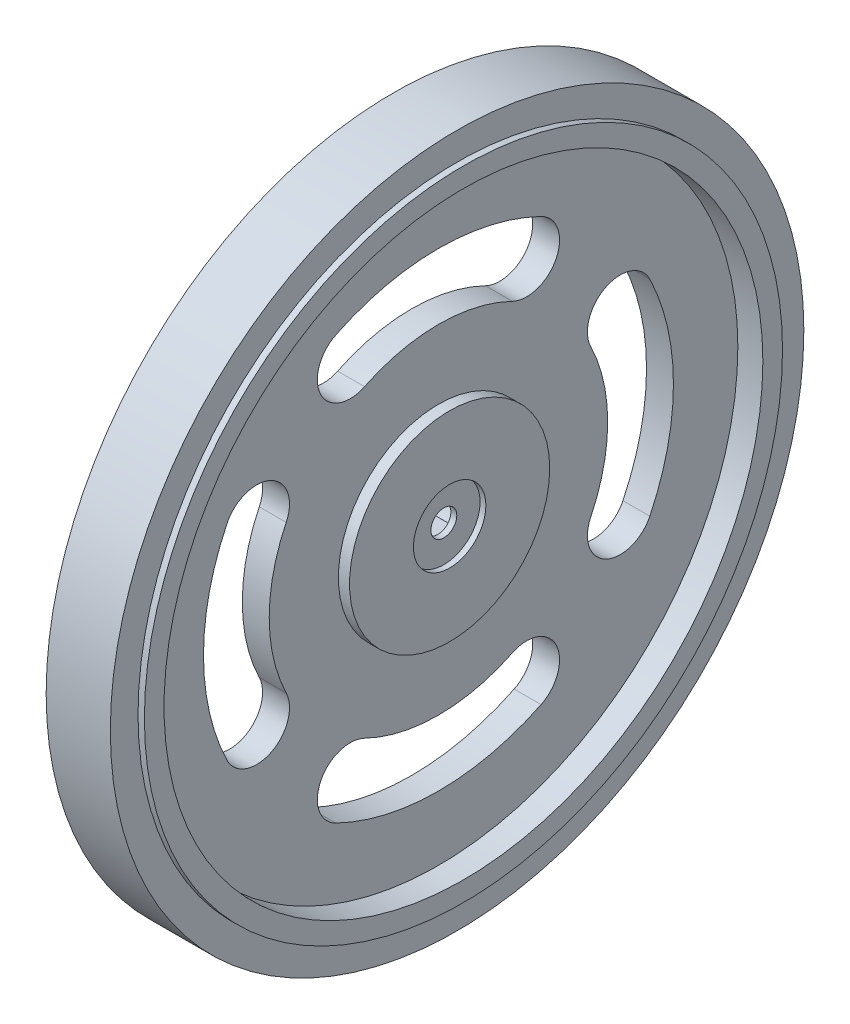
SolidWorks part; units mm, degrees
ref_plane "Front" through (0, 0, 0) normal (0, 0, 1) x (1, 0, 0)
ref_plane "Top" through (0, 0, 0) normal (0, 1, 0) x (1, 0, 0)
ref_plane "Right" through (0, 0, 0) normal (1, 0, 0) x (0, 0, -1)
sketch "Sketch2" plane through (0, 0, 0) normal (0, 0, 1) x (1, 0, 0)
  line L0 (15.9165, 0) -> (-32.1766, 0) construction
  line L1 (2.38, 3.5) -> (2.38, 9.67)
  line L2 (3.715, 30.825) -> (3.1, 30.825)
  line L3 (3.1, 30.825) -> (3.1, 33.5)
  line L4 (3.1, 33.5) -> (-3.1, 33.5)
  line L5 (-3.1, 33.5) -> (-3.1, 30.825)
  line L6 (-3.1, 30.825) -> (-3.715, 30.825)
  line L7 (-3.715, 30.825) -> (-3.715, 28.925)
  line L8 (-3.9, 3.5) -> (1.25, 3.5)
  line L9 (0, 0) -> (0, 36.6612) construction
  line L10 (-3.9, 4.5) -> (-1.3, 4.975)
  line L11 (-1.3, 4.975) -> (-1.3, 28.925)
  line L12 (-1.3, 28.925) -> (-3.715, 28.925)
  line L13 (-3.9, 4.5) -> (-3.9, 3.5)
  line L14 (1.82, 3.5) -> (2.38, 3.5)
  line L16 (1.3, 28.925) -> (1.3, 9.67)
  line L17 (1.3, 9.67) -> (2.38, 9.67)
  line L18 (1.25, 3.5) -> (1.25, 1.25)
  line L19 (1.25, 1.25) -> (1.82, 1.25)
  line L21 (1.82, 1.25) -> (1.82, 3.5)
  line L22 (3.715, 28.925) -> (3.715, 30.825)
  line L23 (1.3, 28.925) -> (3.715, 28.925)
  dimension "D1" = 67
  dimension "D2" = 6.2
  dimension "D3" = 7.43
  dimension "D4" = 7
  dimension "D5" = 0.56
  dimension "D6" = 2.6
  dimension "D7" = 9
  dimension "D8" = 57.85
  dimension "D9" = 61.65
  dimension "D10" = 2.6
  dimension "D11" = 2.5
  dimension "D12" = 19.34
  dimension "D13" = 1.08
  dimension "D14" = 5.15
  dimension "D15" = 9.95
revolve "Revolve1" add sketch "Sketch2" angle 360 about L0
sketch "Sketch3" plane through (1.3, 0, 0) normal (1, 0, 0) x (0, 0, -1)
  line L0 (0, 0) -> (0, 26.49) construction
  circle A0 centre (0, 0) radius 16.35 construction
  circle A1 centre (0, 0) radius 22.7 construction
  circle A2 centre (0, 0) radius 19.525 construction
  arc A3 (-8.525, 17.5656) -> (8.525, 17.5656) centre (0, 0) cw construction
  arc A4 (9.9113, 20.422) -> (-9.9113, 20.422) centre (0, 0) ccw
  arc A5 (7.1387, 14.7092) -> (-7.1387, 14.7092) centre (0, 0) ccw
  arc A6 (7.1387, 14.7092) -> (9.9113, 20.422) centre (8.525, 17.5656) ccw
  arc A7 (-9.9113, 20.422) -> (-7.1387, 14.7092) centre (-8.525, 17.5656) ccw
  arc A8 (17.5656, 8.525) -> (17.5656, -8.525) centre (0, 0) cw construction
  arc A9 (20.422, -9.9113) -> (20.422, 9.9113) centre (0, 0) ccw
  arc A10 (14.7092, -7.1387) -> (14.7092, 7.1387) centre (0, 0) ccw
  arc A11 (14.7092, -7.1387) -> (20.422, -9.9113) centre (17.5656, -8.525) ccw
  arc A12 (20.422, 9.9113) -> (14.7092, 7.1387) centre (17.5656, 8.525) ccw
  arc A13 (8.525, -17.5656) -> (-8.525, -17.5656) centre (0, 0) cw construction
  arc A14 (-9.9113, -20.422) -> (9.9113, -20.422) centre (0, 0) ccw
  arc A15 (-7.1387, -14.7092) -> (7.1387, -14.7092) centre (0, 0) ccw
  arc A16 (-7.1387, -14.7092) -> (-9.9113, -20.422) centre (-8.525, -17.5656) ccw
  arc A17 (9.9113, -20.422) -> (7.1387, -14.7092) centre (8.525, -17.5656) ccw
  arc A18 (-17.5656, -8.525) -> (-17.5656, 8.525) centre (0, 0) cw construction
  arc A19 (-20.422, 9.9113) -> (-20.422, -9.9113) centre (0, 0) ccw
  arc A20 (-14.7092, 7.1387) -> (-14.7092, -7.1387) centre (0, 0) ccw
  arc A21 (-14.7092, 7.1387) -> (-20.422, 9.9113) centre (-17.5656, 8.525) ccw
  arc A22 (-20.422, -9.9113) -> (-14.7092, -7.1387) centre (-17.5656, -8.525) ccw
  point P8 (0, 19.525)
  point P19 (19.525, 0)
  point P27 (0, -19.525)
  point P35 (-19.525, 0)
  dimension "D1" = 32.7
  dimension "D2" = 45.4
  dimension "D3" = 39.05
  dimension "D4" = 23.4
  dimension "D5" = 4
extrude "Cut-Extrude1" cut sketch "Sketch3" against normal up to next
sketch "Sketch4" plane through (1.25, 0, 0) normal (-1, 0, 0) x (0, 0, 1)
  line L0 (-4.2694, 0) -> (6.8461, 0) construction
  line L1 (-2.5709, 2.375) -> (2.5709, 2.375)
  line L2 (-2.5709, -2.375) -> (2.5709, -2.375)
  circle A0 centre (0, 0) radius 3.5 construction
  arc A1 (2.5709, 2.375) -> (-2.5709, 2.375) centre (0, 0) ccw
  arc A2 (2.5709, -2.375) -> (-2.5709, -2.375) centre (0, 0) cw
  dimension "D1" = 4.75
extrude "Boss-Extrude1" add sketch "Sketch4" along normal up to surface (5.15 mm away) up to face at (-3.9, 0, -3.5)
